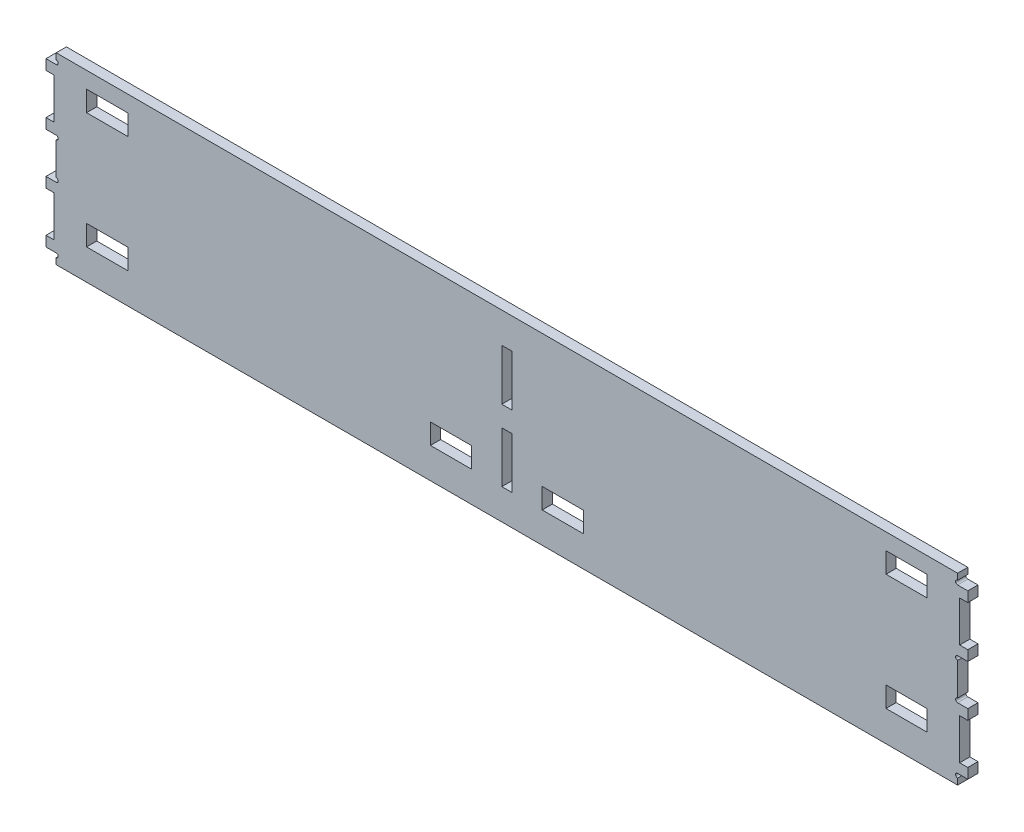
SolidWorks part; units mm, degrees
ref_plane "Front Plane" through (0, 0, 0) normal (0, 0, 1) x (1, 0, 0)
ref_plane "Top Plane" through (0, 0, 0) normal (0, 1, 0) x (1, 0, 0)
ref_plane "Right Plane" through (0, 0, 0) normal (1, 0, 0) x (0, 0, -1)
sketch "Sketch1" plane through (0, 0, 0) normal (0, 0, 1) x (1, 0, 0)
  line L1 (-221, -45) -> (221, -45)
  line L2 (-221, -45) -> (-221, 45)
  line L3 (-221, 45) -> (221, 45)
  line L4 (221, -45) -> (221, 45)
  line L5 (-221, -45) -> (221, 45) construction
  line L6 (-221, 45) -> (221, -45) construction
  point P0 (0, 0)
  dimension "D1" = 90
  dimension "D2" = 442
extrude "Boss-Extrude1" add sketch "Sketch1" along normal blind 5
sketch "Sketch3" plane through (0, 0, 0) normal (0, 0, -1) x (-1, 0, 0)
  line L0 (-221, 45) -> (221, 45) construction
  line L1 (-2.5, 30) -> (2.5, 30)
  line L2 (-2.5, 30) -> (-2.5, 5)
  line L3 (-2.5, 5) -> (2.5, 5)
  line L4 (2.5, 30) -> (2.5, 5)
  line L5 (-2.5, -5) -> (2.5, -5)
  line L6 (-2.5, -5) -> (-2.5, -30)
  line L7 (-2.5, -30) -> (2.5, -30)
  line L8 (2.5, -5) -> (2.5, -30)
  line L9 (221, -45) -> (-221, -45) construction
  line L10 (0, 2.75) -> (0, -2.75) construction
  point P14 (0, -5)
  point P15 (0, 30)
  point P25 (120, -30)
  dimension "D1" = 15
  dimension "D2" = 25
  dimension "D3" = 25
  dimension "D4" = 15
  dimension "D5" = 5
  dimension "D6" = 0
  dimension "D7" = 120
extrude "Cut-Extrude2" cut sketch "Sketch3" against normal through all
sketch "Sketch4" [suppressed] plane through (0, 0, 0) normal (0, 0, -1) x (-1, 0, 0)
  line L0 (-227.5, 30) -> (-227.5, 5) construction
  line L1 (-222.5, 5) -> (-222.5, 30) construction
  line L2 (-227.5, -5) -> (-227.5, -30) construction
  line L3 (-222.5, -30) -> (-222.5, -5) construction
  line L5 (-222.5, -5) -> (-227.5, -5) construction
  circle A0 centre (-227.5, 29) radius 1
  circle A1 centre (-222.5, 29) radius 1
  circle A2 centre (-227.5, 6) radius 1
  circle A3 centre (-222.5, 6) radius 1
  circle A4 centre (-227.5, -6) radius 1
  circle A5 centre (-222.5, -6) radius 1
  circle A6 centre (-227.5, -29) radius 1
  circle A7 centre (-222.5, -29) radius 1
  circle A8 centre (-77.5, 29) radius 1
  circle A9 centre (-72.5, 29) radius 1
  circle A10 centre (-77.5, 6) radius 1
  circle A11 centre (-72.5, 6) radius 1
  circle A12 centre (-77.5, -6) radius 1
  circle A13 centre (-72.5, -6) radius 1
  circle A14 centre (-77.5, -29) radius 1
  circle A15 centre (-72.5, -29) radius 1
  circle A16 centre (72.5, 29) radius 1
  circle A17 centre (77.5, 29) radius 1
  circle A18 centre (72.5, 6) radius 1
  circle A19 centre (77.5, 6) radius 1
  circle A20 centre (72.5, -6) radius 1
  circle A21 centre (77.5, -6) radius 1
  circle A22 centre (72.5, -29) radius 1
  circle A23 centre (77.5, -29) radius 1
  circle A24 centre (222.5, 29) radius 1
  circle A25 centre (227.5, 29) radius 1
  circle A26 centre (222.5, 6) radius 1
  circle A27 centre (227.5, 6) radius 1
  circle A28 centre (222.5, -6) radius 1
  circle A29 centre (227.5, -6) radius 1
  circle A30 centre (222.5, -29) radius 1
  circle A31 centre (227.5, -29) radius 1
  dimension "D1" = 2
extrude "Cut-Extrude3" [suppressed] cut sketch "Sketch4" against normal through all
fillet "Fillet1" [suppressed] radius 1
sketch "Sketch5" plane through (221, 0, 0) normal (1, 0, 0) x (0, 0, -1)
  line L0 (-5, -45) -> (-5, 45) construction
  line L1 (-5, 40) -> (0, 40)
  line L2 (-5, 40) -> (-5, 10)
  line L3 (-5, 10) -> (0, 10)
  line L4 (0, 40) -> (0, 10)
  line L5 (0, -45) -> (0, 45) construction
  line L6 (-5, -45) -> (0, -45) construction
  line L7 (-5, -10) -> (0, -10)
  line L8 (-5, -10) -> (-5, -40)
  line L9 (-5, -40) -> (0, -40)
  line L10 (0, -10) -> (0, -40)
  line L11 (-5, 45) -> (0, 45) construction
  point P16 (-2.5, 45)
  dimension "D1" = 5
  dimension "D2" = 30
  dimension "D3" = 30
  dimension "D4" = 5
extrude "Boss-Extrude2" add sketch "Sketch5" along normal blind 5
sketch "Sketch6" plane through (226, 0, 0) normal (1, 0, 0) x (0, 0, -1)
  line L0 (-5, 40) -> (-5, 10) construction
  line L1 (-5, 35) -> (0, 35)
  line L2 (-5, 35) -> (-5, 15)
  line L3 (-5, 15) -> (0, 15)
  line L4 (0, 35) -> (0, 15)
  line L5 (0, 10) -> (0, 40) construction
  line L6 (-5, -10) -> (-5, -40) construction
  line L7 (-5, -15) -> (0, -15)
  line L8 (-5, -15) -> (-5, -35)
  line L9 (-5, -35) -> (0, -35)
  line L10 (0, -15) -> (0, -35)
  line L11 (0, -40) -> (0, -10) construction
  line L12 (0, 40) -> (-5, 40) construction
  line L13 (-5, 10) -> (0, 10) construction
  line L14 (0, -10) -> (-5, -10) construction
  line L15 (-5, -40) -> (0, -40) construction
  point P20 (-2.5, 10)
  dimension "D1" = 5
  dimension "D2" = 5
  dimension "D3" = 5
  dimension "D4" = 5
extrude "Cut-Extrude4" cut sketch "Sketch6" against normal blind 4
mirror "Mirror1" about plane through (0, 0, 0) normal (1, 0, 0) of "Boss-Extrude2", "Cut-Extrude4"
fillet "Fillet2" [suppressed] radius 1
sketch "Sketch7" plane through (0, 0, 0) normal (0, 0, -1) x (-1, 0, 0)
  line L1 (-221, -10) -> (-221, 10) construction
  line L2 (-221, -45) -> (-221, -40) construction
  line L3 (0, 2.75) -> (0, -2.75) construction
  line L4 (-221, 40) -> (-221, 45) construction
  line L5 (221, 45) -> (221, 40) construction
  circle A1 centre (-221, 9) radius 1
  circle A2 centre (-221, -9) radius 1
  circle A3 centre (-221, -41) radius 1
  circle A4 centre (221, -41) radius 1
  circle A5 centre (221, -9) radius 1
  circle A6 centre (221, 9) radius 1
  circle A8 centre (-221, 41) radius 1
  circle A9 centre (221, 41) radius 1
  dimension "D1" = 2
  dimension "D2" = 2
extrude "Cut-Extrude5" cut sketch "Sketch7" against normal through all
ref_plane "Plane12" through (0, 0, 0) normal (1, 0, 0) x (0, 0, -1)
ref_plane "Plane13" through (0, 3.5, 0) normal (0, 1, 0) x (1, 0, 0)
extrude "Cut-Extrude6" cut sketch "Sketch8" against normal blind 10
sketch "Sketch8" plane through (102.7188, -610.4562, 5) normal (0, 0, 1) x (1, 0, 0)
  line L4 (103.3812, 590.4562) -> (83.1812, 590.4562)
  line L5 (83.1812, 590.4562) -> (83.1812, 580.4562)
  line L6 (103.3812, 580.4562) -> (83.1812, 580.4562)
  line L7 (103.3812, 590.4562) -> (103.3812, 580.4562)
mirror "Mirror2" about plane through (0, 0, 0) normal (1, 0, 0) of "Cut-Extrude6"
extrude "Cut-Extrude7" cut sketch "Sketch9" against normal blind 300
sketch "Sketch9" plane through (102.7188, -610.4562, 228.5) normal (0, 0, 1) x (1, 0, 0)
  line L4 (-120.0188, 590.4562) -> (-140.2188, 590.4562)
  line L5 (-140.2188, 590.4562) -> (-140.2188, 580.4562)
  line L6 (-120.0188, 580.4562) -> (-140.2188, 580.4562)
  line L7 (-120.0188, 590.4562) -> (-120.0188, 580.4562)
  line L80 (123.2812, 615.4562) -> (123.2812, 620.4562)
  line L81 (123.2812, 620.4562) -> (119.2812, 620.4562)
  line L82 (119.2812, 620.4562) -> (119.2812, 635.4562)
  line L83 (119.2812, 635.4562) -> (123.2812, 635.4562)
  line L84 (123.2812, 635.4562) -> (123.2812, 640.4562)
  line L85 (123.2812, 640.4562) -> (118.2812, 640.4562)
  line L86 (118.2812, 640.4562) -> (118.2812, 645.4562)
  line L87 (118.2812, 645.4562) -> (-100.1188, 645.4562)
  line L88 (-100.1188, 645.4562) -> (-100.1188, 605.4562)
  line L89 (-100.1188, 605.4562) -> (-105.3188, 605.4562)
  line L90 (-105.3188, 605.4562) -> (-105.3188, 645.4562)
  line L91 (-105.3188, 645.4562) -> (-323.7188, 645.4562)
  line L92 (-323.7188, 645.4562) -> (-323.7188, 640.4562)
  line L93 (-323.7188, 640.4562) -> (-328.7188, 640.4562)
  line L94 (-328.7188, 640.4562) -> (-328.7188, 635.4562)
  line L95 (-328.7188, 635.4562) -> (-324.7188, 635.4562)
  line L96 (-324.7188, 635.4562) -> (-324.7188, 620.4562)
  line L97 (-324.7188, 620.4562) -> (-328.7188, 620.4562)
  line L98 (-328.7188, 620.4562) -> (-328.7188, 615.4562)
  line L99 (-328.7188, 615.4562) -> (-323.7188, 615.4562)
  line L100 (-323.7188, 615.4562) -> (-323.7188, 605.5562)
  line L101 (-323.7188, 605.5562) -> (-328.7188, 605.5562)
  line L102 (-328.7188, 605.5562) -> (-328.7188, 600.5562)
  line L103 (-328.7188, 600.5562) -> (-324.7188, 600.5562)
  line L104 (-324.7188, 600.5562) -> (-324.7188, 585.5562)
  line L105 (-324.7188, 585.5562) -> (-328.7188, 585.5562)
  line L106 (-328.7188, 585.5562) -> (-328.7188, 580.5562)
  line L107 (-328.7188, 580.5562) -> (-323.7188, 580.5562)
  line L108 (-323.7188, 580.5562) -> (-323.7188, 565.4562)
  line L109 (-323.7188, 565.4562) -> (118.2812, 565.4562)
  line L110 (118.2812, 565.4562) -> (118.2812, 580.5562)
  line L111 (118.2812, 580.5562) -> (123.2812, 580.5562)
  line L112 (123.2812, 580.5562) -> (123.2812, 585.5562)
  line L113 (123.2812, 585.5562) -> (119.2812, 585.5562)
  line L114 (119.2812, 585.5562) -> (119.2812, 600.5562)
  line L115 (119.2812, 600.5562) -> (123.2812, 600.5562)
  line L116 (123.2812, 600.5562) -> (123.2812, 605.5562)
  line L117 (123.2812, 605.5562) -> (118.2812, 605.5562)
  line L118 (118.2812, 605.5562) -> (118.2812, 615.4562)
  line L119 (118.2812, 615.4562) -> (123.2812, 615.4562)
mirror "Mirror3" about plane through (0, 0, 0) normal (1, 0, 0) of "Cut-Extrude7"
mirror "Mirror4" about plane through (0, 3.5, 0) normal (0, 1, 0) of "Mirror2", "Cut-Extrude6"
